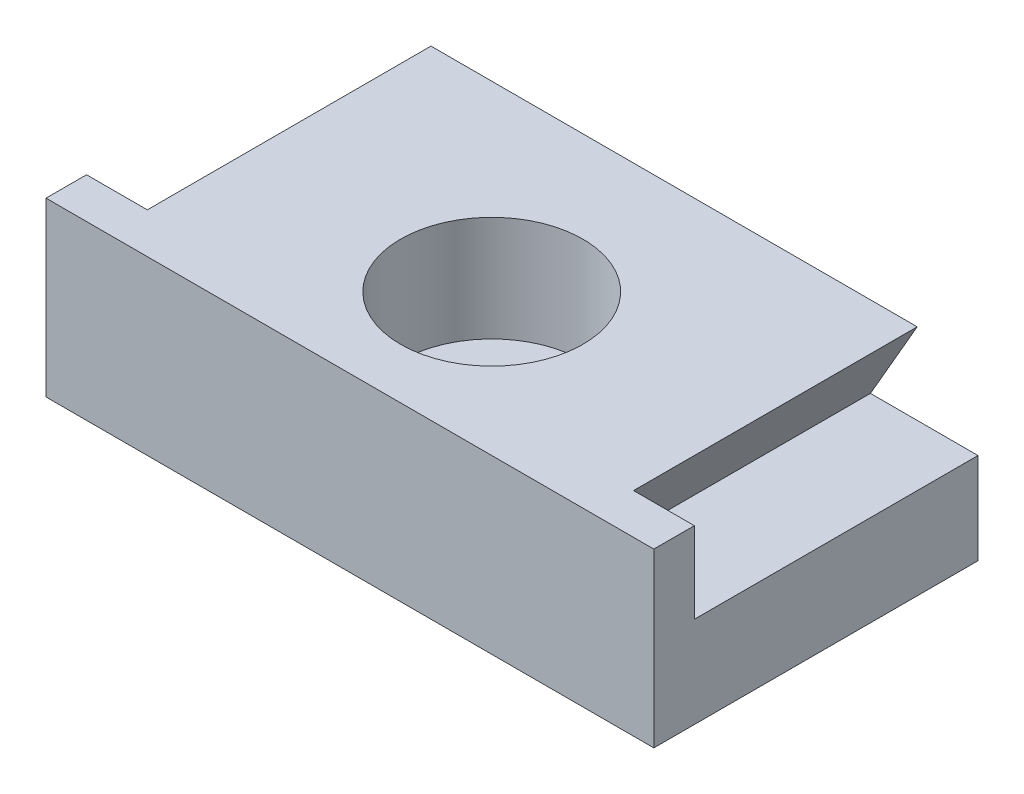
SolidWorks part; units mm, degrees
ref_plane "Front Plane" through (0, 0, 0) normal (0, 0, 1) x (1, 0, 0)
ref_plane "Top Plane" through (0, 0, 0) normal (0, 1, 0) x (1, 0, 0)
ref_plane "Right Plane" through (0, 0, 0) normal (1, 0, 0) x (0, 0, -1)
sketch "Sketch1" plane through (0, 0, 0) normal (0, 1, 0) x (1, 0, 0)
  line L1 (0, 0) -> (30, 0)
  line L2 (0, 0) -> (0, 16)
  line L3 (0, 16) -> (30, 16)
  line L4 (30, 0) -> (30, 16)
  dimension "D1" = 30
  dimension "D2" = 16
extrude "Boss-Extrude1" add sketch "Sketch1" along normal blind 8.5
sketch "Sketch2" plane through (0, 8.5, 0) normal (0, 1, 0) x (1, 0, 0)
  line L0 (0, 0) -> (30, 0) construction
  circle A0 centre (15, 7) radius 4.5
  point P5 (15, 0)
  dimension "D1" = 9
  dimension "D2" = 7
extrude "Cut-Extrude1" cut sketch "Sketch2" against normal blind 5.2
sketch "Sketch3" plane through (0, 3.3, 0) normal (0, 1, 0) x (1, 0, 0)
  circle A0 centre (15, 7) radius 2.65
  circle A1 centre (15, 7) radius 4.5 construction
  circle A2 centre (15, 7) radius 4.5 construction
  dimension "D1" = 5.3
extrude "Cut-Extrude2" cut sketch "Sketch3" against normal through all
sketch "Sketch4" plane through (0, 0, -16) normal (0, 0, -1) x (-1, 0, 0)
  line L0 (-27, 8.5) -> (-24.69, 4.4989)
  line L1 (-30, 8.5) -> (-30, 0) construction
  line L2 (-24.69, 4.4989) -> (-30, 4.4989)
  line L3 (-30, 0) -> (0, 0) construction
  line L4 (-30, 8.5) -> (0, 8.5) construction
  line L5 (-30, 4.4989) -> (-30, 8.5)
  line L6 (-30, 8.5) -> (-27, 8.5)
  line L7 (-15, 8.5) -> (-15, 0) construction
  line L8 (0, 8.5) -> (-3, 8.5)
  line L9 (0, 4.4989) -> (0, 8.5)
  line L10 (-5.31, 4.4989) -> (0, 4.4989)
  line L11 (-3, 8.5) -> (-5.31, 4.4989)
  dimension "D1" = 4.0011
  dimension "D2" = 3
  dimension "D3" = 60
extrude "Cut-Extrude3" cut sketch "Sketch4" against normal blind 14
sketch "Sketch5" plane through (0, 0, -16) normal (0, 0, -1) x (-1, 0, 0)
  line L2 (0, 8.5) -> (0, 0) construction
  line L3 (-15, 8.5) -> (-15, 0) construction
  line L4 (-30, 0) -> (0, 0) construction
  line L5 (-27, 8.5) -> (-3, 8.5) construction
  circle A0 centre (-21.5, 4.25) radius 2.1
  circle A1 centre (-8.5, 4.25) radius 2.1
  point P10 (0, 4.25)
  dimension "D1" = 4.2
  dimension "D2" = 6.5
  dimension "D3" = 4.25
extrude "Cut-Extrude4" cut sketch "Sketch5" against normal blind 7
sketch "Sketch6" plane through (0, 0, 0) normal (0, -1, 0) x (1, 0, 0)
  line L0 (19.8808, -7) -> (10.1192, -7) construction
  circle A0 centre (10.1192, -7) radius 1.1
  circle A1 centre (19.8808, -7) radius 1.1
  circle A2 centre (15, -7) radius 2.65 construction
  circle A3 centre (15, -7) radius 2.65 construction
  point P8 (15, -7)
  dimension "D1" = 2.2
extrude "Cut-Extrude5" cut sketch "Sketch6" against normal blind 2.5
